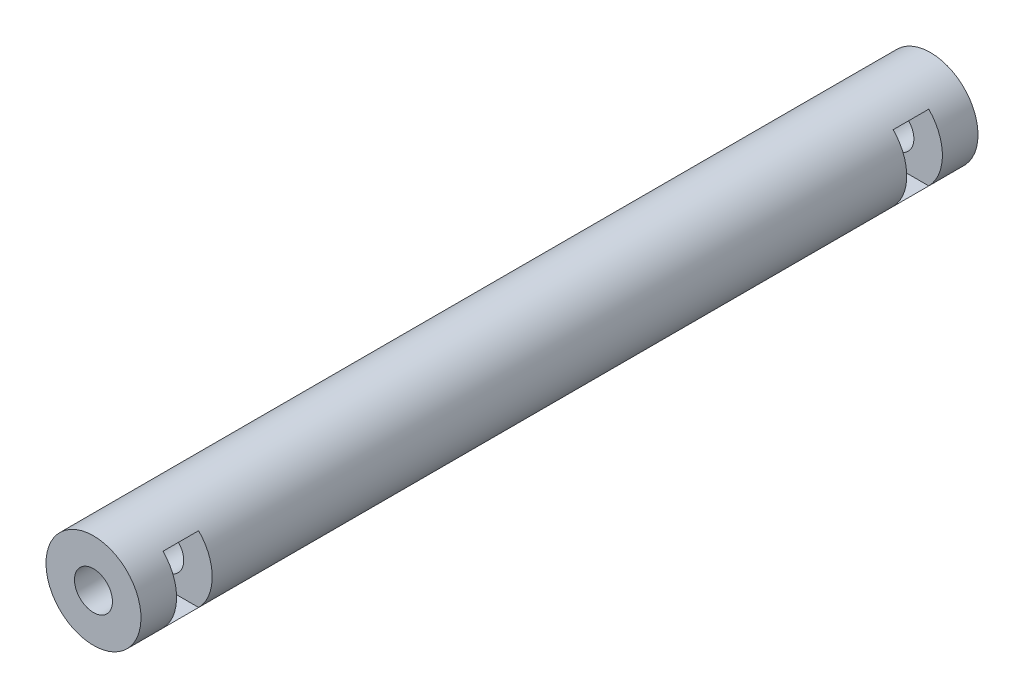
SolidWorks part; units mm, degrees
ref_plane "正面" through (0, 0, 0) normal (0, 0, 1) x (1, 0, 0)
ref_plane "平面" through (0, 0, 0) normal (0, 1, 0) x (1, 0, 0)
ref_plane "右側面" through (0, 0, 0) normal (1, 0, 0) x (0, 0, -1)
sketch "ｽｹｯﾁ1" plane through (0, 0, 0) normal (0, 0, 1) x (1, 0, 0)
  circle A0 centre (2, 37) radius 4
  circle A1 centre (2, 37) radius 1.6 construction
  point P3 (0, 0)
  dimension "D1" = 8
extrude "ﾎﾞｽ - 押し出し1" add sketch "ｽｹｯﾁ1" along normal up to surface (70.4917 mm away)
sketch "ｽｹｯﾁ2" plane through (0, 0, 0) normal (0, 0, -1) x (-1, 0, 0)
  circle A0 centre (-2, 37) radius 1.6 construction
  circle A1 centre (-2, 37) radius 1.6
extrude "ｶｯﾄ - 押し出し1" cut sketch "ｽｹｯﾁ2" against normal through all both and the other way through all
sketch "ｽｹｯﾁ3" plane through (0, 0, 0) normal (1, 0, 0) x (0, 0, -1)
  line L0 (0, 33) -> (0, 41) construction
  line L1 (-6, 39.8) -> (-3, 39.8)
  line L2 (-6, 39.8) -> (-6, 34.2)
  line L3 (-6, 34.2) -> (-3, 34.2)
  line L4 (-3, 39.8) -> (-3, 34.2)
  line L10 (0, 50) -> (0, -50) construction
  line L11 (-70.4917, 37) -> (0, 37) construction
  point P11 (-6, 37)
  dimension "D1" = 5.6
  dimension "D2" = 3
  dimension "D3" = 90
  dimension "D4" = 6
extrude "ｶｯﾄ - 押し出し2" cut sketch "ｽｹｯﾁ3" against normal through all both from offset 15
sketch "ｽｹｯﾁ4" plane through (0, 0, 70.4917) normal (0, 0, 1) x (1, 0, 0)
  arc A0 (4.9591, 39.6914) -> (-0.6518, 39.9947) centre (0, 0) ccw
  circle A1 centre (2, 37) radius 4 construction
  circle A2 centre (0, 0) radius 32.5 construction
  arc A3 (-0.6518, 39.9947) -> (4.9591, 39.6914) centre (2, 37) ccw
  dimension "D1" = 40
extrude "ｶｯﾄ - 押し出し3" [suppressed] cut sketch "ｽｹｯﾁ4" against normal through all both
ref_plane "平面1" through (0, 0, 35.2458) normal (0, 0, -1) x (-1, 0, 0)
mirror "ﾐﾗｰ1" about plane through (0, 0, 35.2458) normal (0, 0, -1) of "ｶｯﾄ - 押し出し2"
